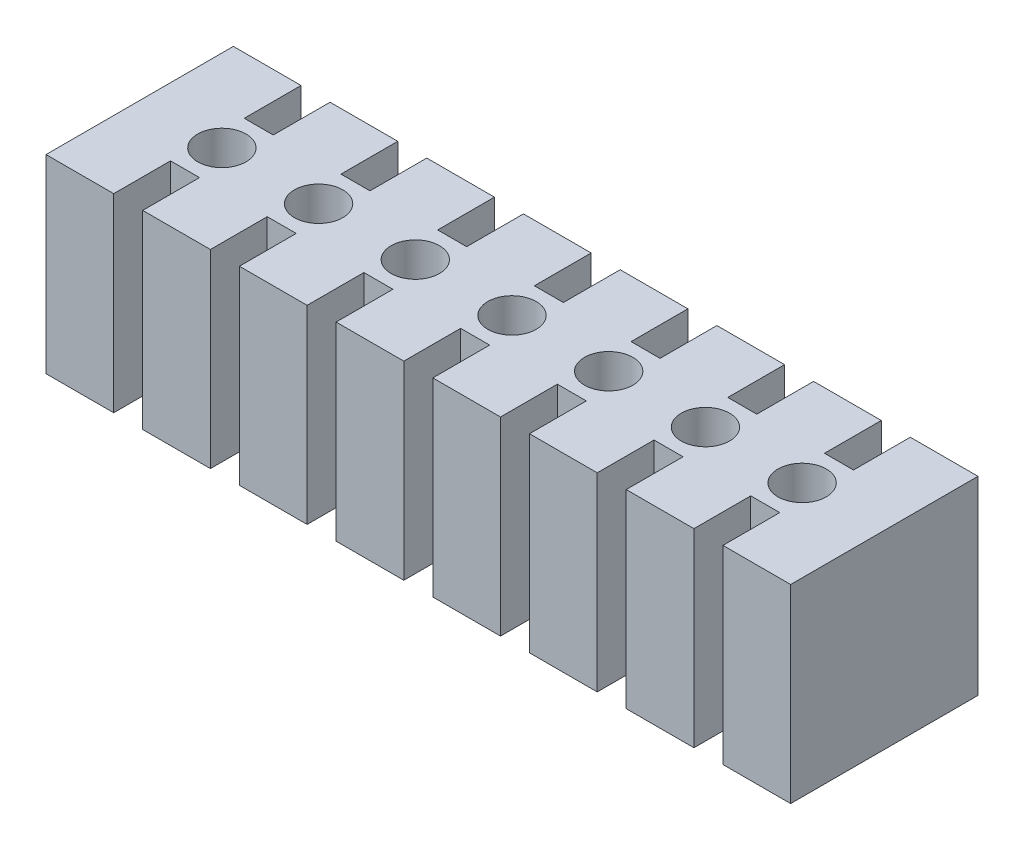
SolidWorks part; units mm, degrees
ref_plane "Front Plane" through (0, 0, 0) normal (0, 0, 1) x (1, 0, 0)
ref_plane "Top Plane" through (0, 0, 0) normal (0, 1, 0) x (1, 0, 0)
ref_plane "Right Plane" through (0, 0, 0) normal (1, 0, 0) x (0, 0, -1)
sketch "Sketch1" plane through (0, 0, 0) normal (0, 1, 0) x (1, 0, 0)
  line L0 (0, 10.8) -> (0, 15.5)
  line L1 (0, 0) -> (5.6, 0)
  line L2 (0, 0) -> (0, 4.7)
  line L3 (0, 15.5) -> (5.6, 15.5)
  line L4 (5.6, 0) -> (5.6, 4.7)
  line L5 (5.6, 10.8) -> (6.8, 10.8)
  line L7 (5.6, 4.7) -> (6.8, 4.7)
  line L8 (6.8, 10.8) -> (6.8, 9.75)
  line L9 (0, 10.8) -> (-1.2, 10.8)
  line L11 (0, 4.7) -> (-1.2, 4.7)
  line L12 (-1.2, 10.8) -> (-1.2, 9.75)
  line L13 (5.6, 10.8) -> (5.6, 15.5)
  line L14 (-1.2, 5.75) -> (-1.2, 4.7)
  line L15 (6.8, 5.75) -> (6.8, 4.7)
  arc A0 (6.8, 9.75) -> (6.8, 5.75) centre (6.8, 7.75) ccw
  arc A1 (-1.2, 9.75) -> (-1.2, 5.75) centre (-1.2, 7.75) cw
  dimension "D5" = 2
  dimension "D1" = 5.6
  dimension "D2" = 15.5
  dimension "D3" = 8
  dimension "D4" = 6.1
extrude "Boss-Extrude1" add sketch "Sketch1" along normal blind 15.7
pattern_linear "LPattern1" count 8 spacing 8 along (1, 0, 0) of "Boss-Extrude1"
sketch "Sketch2" plane through (0, 15.7, 0) normal (0, 1, 0) x (1, 0, 0)
  line L1 (0, 10.8) -> (-1.2, 10.8)
  line L2 (0, 10.8) -> (0, 4.7)
  line L3 (0, 4.7) -> (-1.2, 4.7)
  line L4 (-1.2, 10.8) -> (-1.2, 4.7)
  line L5 (61.6, 10.8) -> (62.8, 10.8)
  line L6 (61.6, 10.8) -> (61.6, 4.7)
  line L7 (61.6, 4.7) -> (62.8, 4.7)
  line L8 (62.8, 10.8) -> (62.8, 4.7)
extrude "Cut-Extrude1" cut sketch "Sketch2" against normal through all
sketch "Sketch3" plane through (0, 15.7, 0) normal (0, 1, 0) x (1, 0, 0)
  line L1 (0, 6.15) -> (0.8, 6.15)
  line L2 (0, 6.15) -> (0, 9.35)
  line L3 (0, 9.35) -> (0.8, 9.35)
  line L4 (0.8, 6.15) -> (0.8, 9.35)
  line L5 (61.6, 9.35) -> (60.8, 9.35)
  line L6 (61.6, 9.35) -> (61.6, 6.15)
  line L7 (61.6, 6.15) -> (60.8, 6.15)
  line L8 (60.8, 9.35) -> (60.8, 6.15)
  arc A0 (0, 6.15) -> (0, 9.35) centre (-1.2, 7.75) ccw construction
  arc A1 (61.6, 9.35) -> (61.6, 6.15) centre (62.8, 7.75) ccw construction
extrude "Boss-Extrude2" add sketch "Sketch3" against normal up to surface (15.7 mm away) up to face at (30.8, 0, -7.75)
